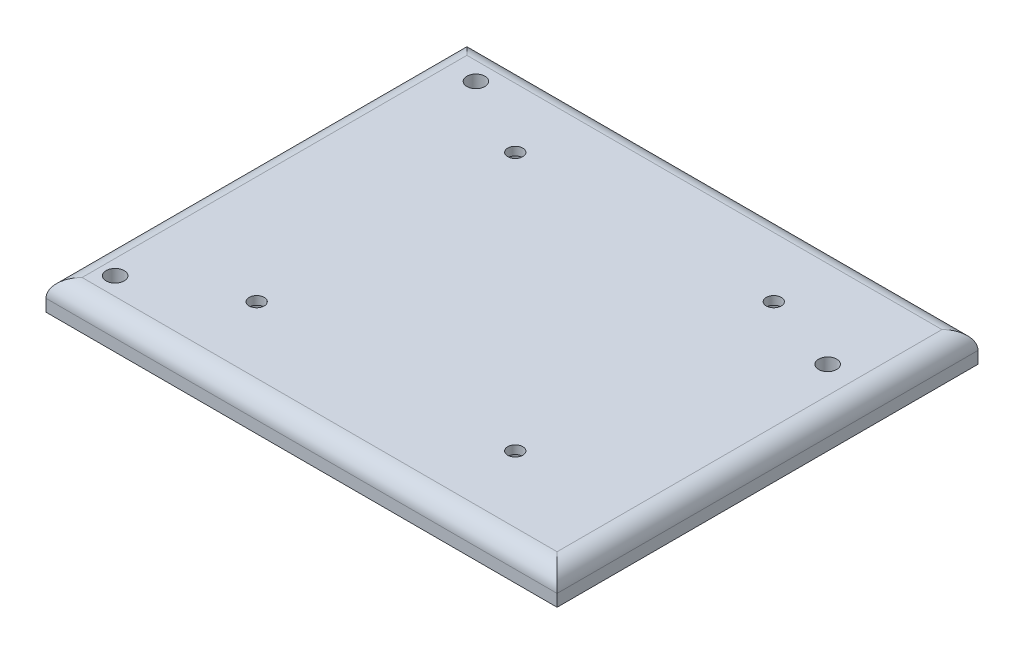
SolidWorks part; units mm, degrees
ref_plane "Front Plane" through (0, 0, 0) normal (0, 0, 1) x (1, 0, 0)
ref_plane "Top Plane" through (0, 0, 0) normal (0, 1, 0) x (1, 0, 0)
ref_plane "Right Plane" through (0, 0, 0) normal (1, 0, 0) x (0, 0, -1)
sketch "Sketch1" plane through (0, 0, 0) normal (0, 1, 0) x (1, 0, 0)
  line L0 (35, 17.5) -> (-35, 17.5) construction
  line L1 (42.5, -35) -> (-42.5, -35)
  line L2 (42.5, -35) -> (42.5, 35)
  line L3 (42.5, 35) -> (-42.5, 35)
  line L4 (-42.5, -35) -> (-42.5, 35)
  line L5 (42.5, -35) -> (-42.5, 35) construction
  line L6 (42.5, 35) -> (-42.5, -35) construction
  line L7 (-35, 17.5) -> (-35, 29) construction
  line L8 (-35, 29) -> (-35, -29) construction
  line L9 (-35, -29) -> (-37, -29) construction
  circle A0 centre (-35, 29) radius 1.5
  circle A1 centre (-37, -29) radius 1.5
  circle A2 centre (35, 17.5) radius 1.5
  point P0 (0, 0)
  dimension "D6" = 3
  dimension "D7" = 7.5
  dimension "D1" = 70
  dimension "D2" = 85
  dimension "D3" = 70
  dimension "D4" = 11.5
  dimension "D5" = 58
  dimension "D8" = 6
  dimension "D9" = 2
extrude "Boss-Extrude1" add sketch "Sketch1" along normal blind 5
sketch "Sketch3" plane through (0, 5, 0) normal (0, 1, 0) x (1, 0, 0)
  line L0 (-42.5, 0.5372) -> (42.5, 0.5372) construction
  line L1 (-42.5, 35) -> (-42.5, -35) construction
  line L2 (42.5, -35) -> (42.5, 35) construction
  line L3 (0, 35) -> (0, -35) construction
  line L4 (42.5, 35) -> (-42.5, 35) construction
  line L5 (-42.5, -35) -> (42.5, -35) construction
  circle A0 centre (-21.5, 22.0372) radius 1.25
  circle A1 centre (21.5, 22.0372) radius 1.25
  circle A2 centre (-21.5, -20.9628) radius 1.25
  circle A3 centre (21.5, -20.9628) radius 1.25
  point P14 (0, 0)
  point P16 (-19.9103, 10.1241)
  dimension "D3" = 2.5
  dimension "D1" = 21.5
  dimension "D2" = 21.5
extrude "Cut-Extrude1" cut sketch "Sketch3" against normal up to next
sketch "Sketch4" plane through (0, 0, 0) normal (0, -1, 0) x (1, 0, 0)
  circle A0 centre (-21.5, 20.9628) radius 3
  circle A1 centre (21.5, 20.9628) radius 3
  circle A2 centre (21.5, -22.0372) radius 3
  circle A3 centre (-21.5, -22.0372) radius 3
  dimension "D1" = 6
extrude "Cut-Extrude2" cut sketch "Sketch4" against normal blind 3.6
fillet "Fillet2" radius 3 4 edges at (42.5, 5, 0) (0, 5, -35) (-42.5, 5, 0) (0, 5, 35)
